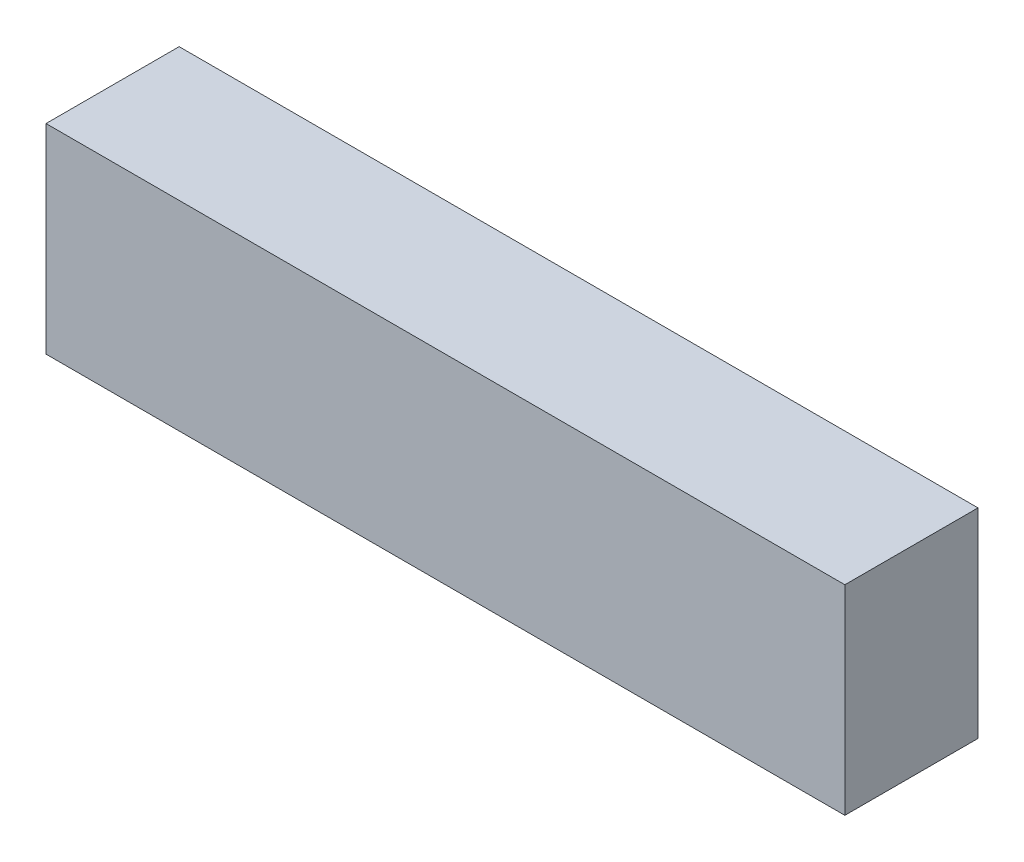
SolidWorks part; units mm, degrees
ref_plane "Alzado" through (0, 0, 0) normal (0, 0, 1) x (1, 0, 0)
ref_plane "Planta" through (0, 0, 0) normal (0, 1, 0) x (1, 0, 0)
ref_plane "Vista lateral" through (0, 0, 0) normal (1, 0, 0) x (0, 0, -1)
sketch "Croquis1" plane through (0, 0, 0) normal (0, 0, 1) x (1, 0, 0)
  line L1 (-152.4, 38.1) -> (152.4, 38.1)
  line L2 (-152.4, 38.1) -> (-152.4, -38.1)
  line L3 (-152.4, -38.1) -> (152.4, -38.1)
  line L4 (152.4, 38.1) -> (152.4, -38.1)
  line L5 (-152.4, 38.1) -> (152.4, -38.1) construction
  line L6 (-152.4, -38.1) -> (152.4, 38.1) construction
  point P0 (0, 0)
  dimension "D1" = 304.8
  dimension "D2" = 76.2
extrude "Saliente-Extruir1" add sketch "Croquis1" along normal blind 50.8
